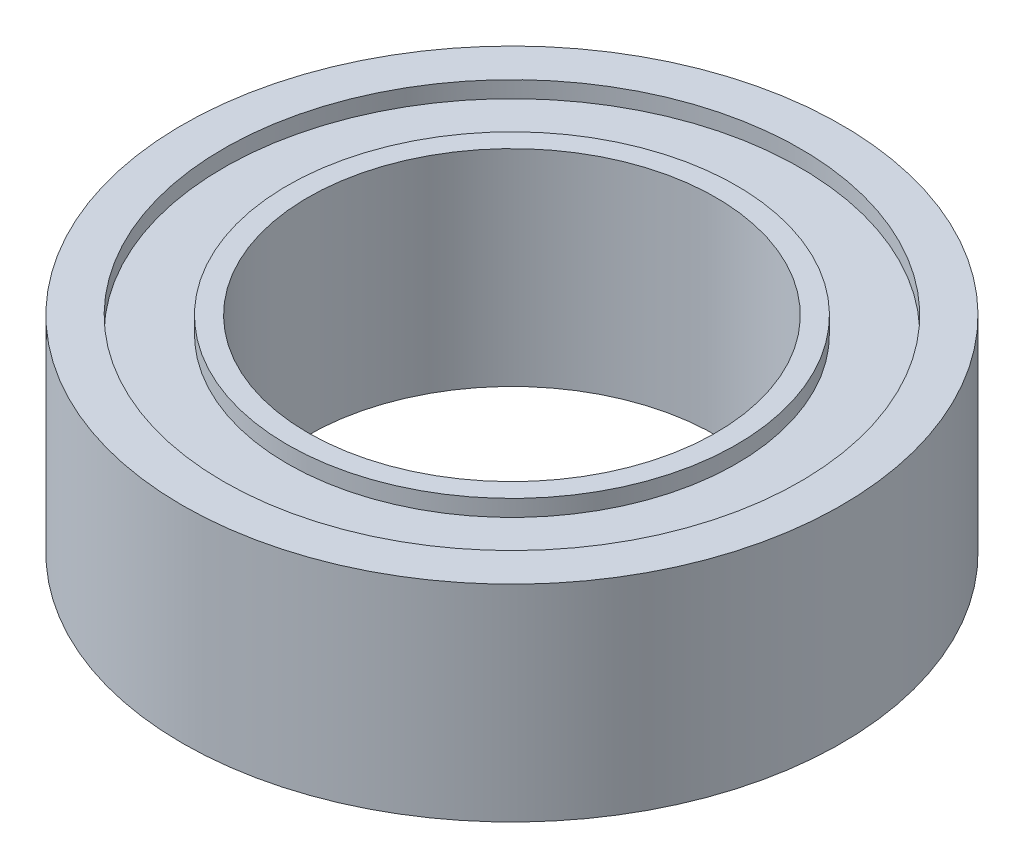
SolidWorks part; units mm, degrees
ref_plane "Спереди" through (0, 0, 0) normal (0, 0, 1) x (1, 0, 0)
ref_plane "Сверху" through (0, 0, 0) normal (0, 1, 0) x (1, 0, 0)
ref_plane "Справа" through (0, 0, 0) normal (1, 0, 0) x (0, 0, -1)
sketch "Эскиз1" plane through (0, 0, 0) normal (0, 1, 0) x (1, 0, 0)
  circle A0 centre (0, 0) radius 4
  circle A1 centre (0, 0) radius 2.475
extrude "Бобышка-Вытянуть1" add sketch "Эскиз1" along normal blind 2.5
sketch "Эскиз2" plane through (0, 2.5, 0) normal (0, 1, 0) x (1, 0, 0)
  circle A0 centre (0, 0) radius 2.725
  circle A1 centre (0, 0) radius 2.475 construction
  circle A2 centre (0, 0) radius 3.2
  circle A3 centre (0, 0) radius 4 construction
  circle A4 centre (0, 0) radius 3.5
  dimension "D1" = 0.25
  dimension "D2" = 0.8
  dimension "D3" = 0.5
extrude "Вырез-Вытянуть1" cut sketch "Эскиз2" against normal blind 0.2 contours A2 A0 | A4 A2
sketch "Эскиз3" plane through (0, 0, 0) normal (0, -1, 0) x (1, 0, 0)
  circle A0 centre (0, 0) radius 2.725
  circle A1 centre (0, 0) radius 3.5
extrude "Вырез-Вытянуть2" cut sketch "Эскиз3" against normal blind 0.2
